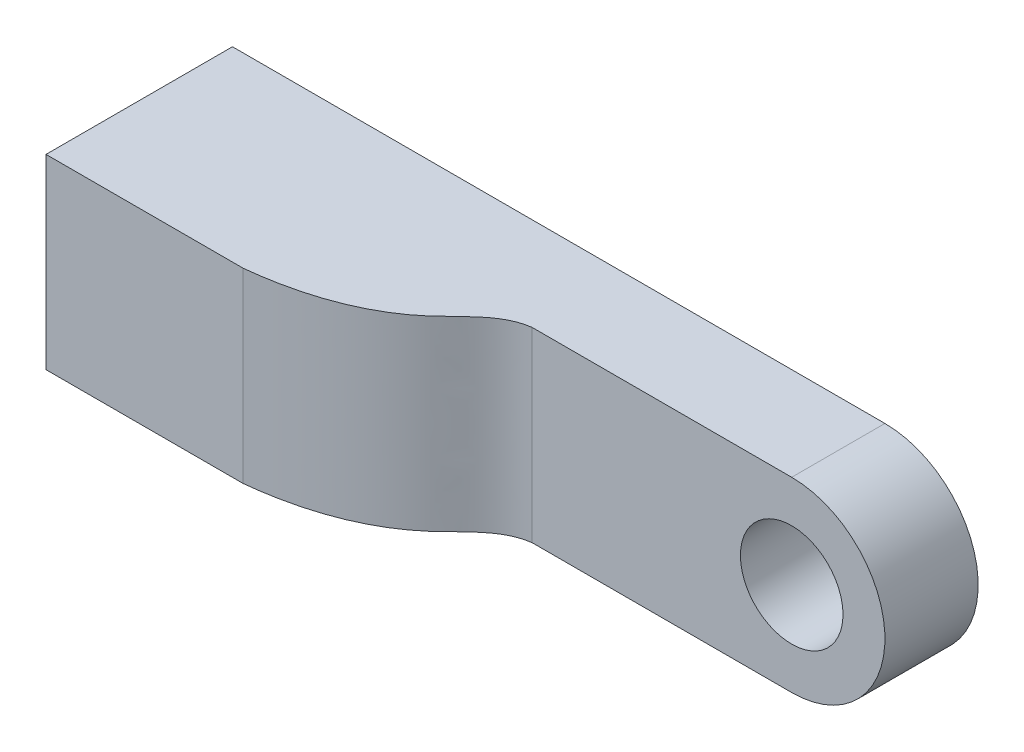
SolidWorks part; units mm, degrees
ref_plane "前视基准面" through (0, 0, 0) normal (0, 0, 1) x (1, 0, 0)
ref_plane "上视基准面" through (0, 0, 0) normal (0, 1, 0) x (1, 0, 0)
ref_plane "右视基准面" through (0, 0, 0) normal (1, 0, 0) x (0, 0, -1)
sketch "草图2" plane through (0, 0, 0) normal (0, 0, 1) x (1, 0, 0)
  line L0 (5.9985, 1.8543) -> (-7.9985, 1.8543)
  line L1 (-7.9985, 1.8543) -> (-7.9985, -2.1457)
  line L2 (-7.9985, -2.1457) -> (5.9985, -2.1457)
  circle A0 centre (5.9985, -0.1457) radius 1.1
  arc A1 (5.9985, 1.8543) -> (5.9985, -2.1457) centre (5.9985, -0.1457) cw
extrude "凸台-拉伸1" add sketch "草图2" along normal blind 4
sketch "草图4" plane through (-7.9985, 0, 0) normal (-1, 0, 0) x (0, 0, 1)
  line L0 (0, -0.1457) -> (2, -0.1457) construction
  line L1 (0, 1.8543) -> (0, -2.1457) construction
  circle A2 centre (2, -0.1457) radius 1
extrude "切除-拉伸1" cut sketch "草图4" against normal blind 5 contours A2
sketch "草图6" plane through (0, 1.8543, 0) normal (0, 1, 0) x (1, 0, 0)
  line L1 (8.8459, -2) -> (-0.3558, -2) construction
  line L2 (8.8459, -2) -> (8.8459, -9.3463) construction
  line L3 (8.8459, -9.3463) -> (-0.3558, -9.3463) construction
  line L4 (-0.3558, -2) -> (-0.3558, -9.3463) construction
  line L5 (5.9985, 0) -> (-7.9985, 0) construction
  line L6 (5.9985, -4) -> (-7.9985, -4) construction
  line L7 (0.4302, -2) -> (8.4223, -2)
  line L8 (8.4223, -2) -> (8.4223, -4.4835)
  line L9 (8.4223, -4.4835) -> (-3.7674, -4)
  spline S0 degree 3 poles (-3.7674, -4) (-2.7562, -3.8918) (-1.1231, -3.429) (-0.1485, -2.0772) (0.4302, -2) knots 0 0 0 0 0.65676 1 1 1 1
  dimension "D1" = 2
extrude "切除-拉伸2" cut sketch "草图6" against normal blind 5
